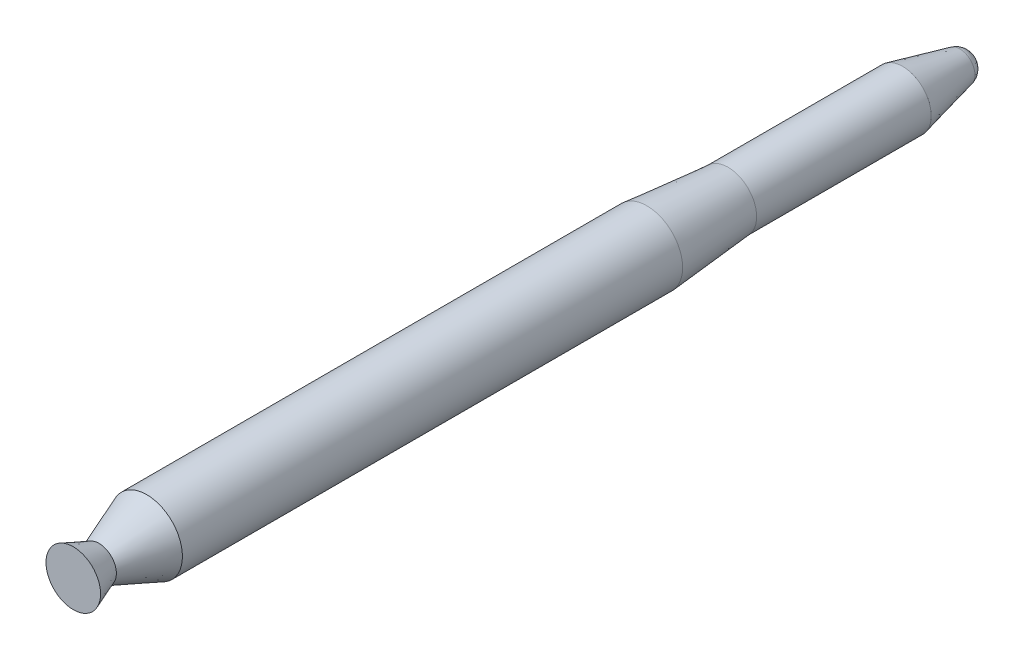
SolidWorks part; units mm, degrees
ref_plane "Front Plane"
ref_plane "Top Plane" through (0, 0, 0) normal (0, 1, 0) x (1, 0, 0)
ref_plane "Right Plane" through (0, 0, 0) normal (1, 0, 0) x (0, 0, -1)
sketch "Sketch1" plane through (0, 0, 0) normal (0, 1, 0) x (1, 0, 0)
  line L0 (0, 0) -> (-25956.1223, 0) construction
  line L1 (0, 0) -> (0, 25956.1223) construction
  line L3 (2500, 0) -> (2500, 35000)
  line L5 (0, 35000) -> (0, 0)
  line L6 (2500, 35000) -> (2000, 40678.0278) construction
  line L7 (2000, 40678.0278) -> (2000, 45962.4129)
  line L9 (0, 49300) -> (0, 40678.0278)
  line L11 (2500, 35000) -> (2000, 40678.0278)
  line L12 (0, 40678.0278) -> (0, 35000)
  line L13 (2000, 45962.4129) -> (2000, 52893.4129)
  line L14 (0, -3336.5871) -> (0, 0)
  line L15 (1215, -3336.5871) -> (0, -3336.5871)
  line L16 (0, 57663.4129) -> (0, 49300)
  line L17 (2000, 52893.4129) -> (1060.3974, 56895.743)
  line L18 (1215, -3336.5871) -> (2500, 0)
  arc A0 (1060.3974, 56895.743) -> (0, 57663.4129) centre (86.8653, 56667.1928) ccw
  dimension "D10" = 1000
  dimension "D1" = 35000
  dimension "D2" = 5000
  dimension "D3" = 5700
  dimension "D4" = 4000
  dimension "D5" = 2430
  dimension "D6" = 6931
  dimension "D7" = 4770
  dimension "D8" = 21.063
  dimension "D9" = 61000
  dimension "D11" = 13.212
revolve "Revolve1" add sketch "Sketch1" angle 360 about L1
sketch "Sketch2" plane through (0, 0, 0) normal (0, 1, 0) x (1, 0, 0)
  line L0 (0, 0) -> (0, -50000) construction
  line L1 (0, 0) -> (50000, 0) construction
  line L2 (1215, -3336.5871) -> (1909.0971, -5136.5871)
  line L3 (1909.0971, -5136.5871) -> (0, -5136.5871)
  line L4 (0, -5136.5871) -> (0, -3336.5871)
  line L5 (0, -3336.5871) -> (1215, -3336.5871)
  dimension "D1" = 1800
revolve "Revolve2" add sketch "Sketch2" angle 360 about L0
